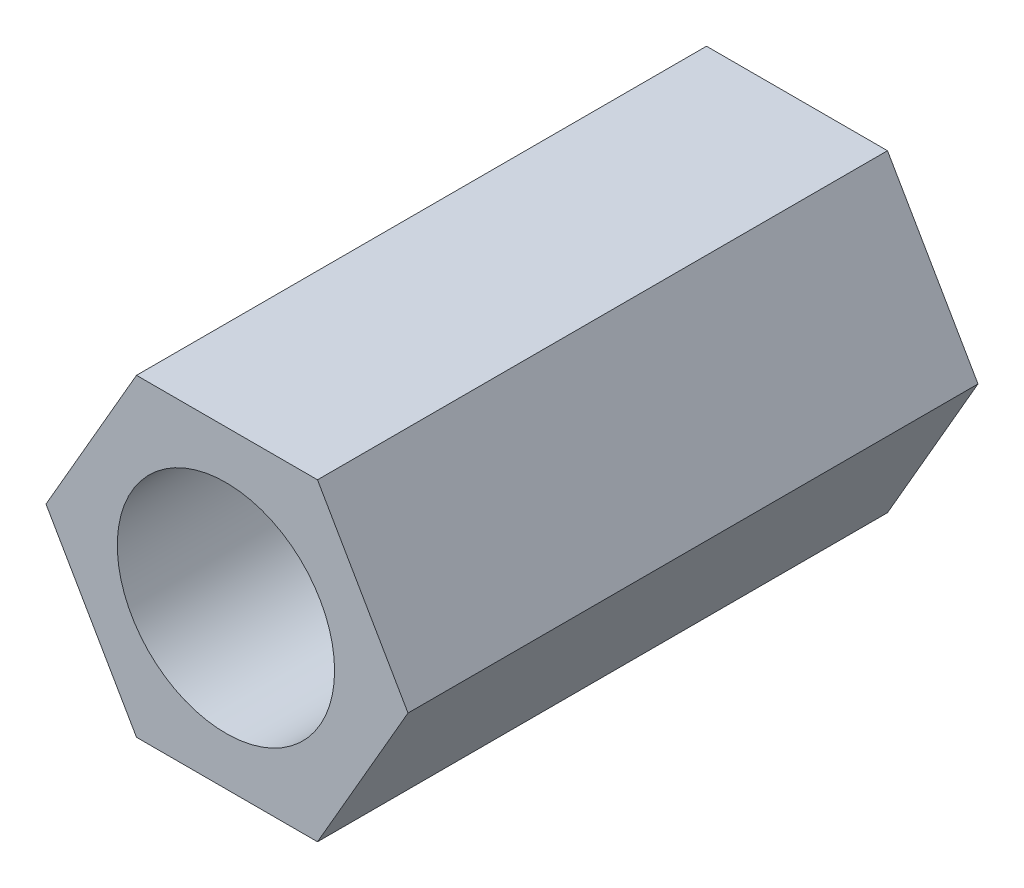
SolidWorks part; units mm, degrees
material "7075-T6 (SN)"
ref_plane "Front Plane" through (0, 0, 0) normal (0, 0, 1) x (1, 0, 0)
ref_plane "Top Plane" through (0, 0, 0) normal (0, 1, 0) x (1, 0, 0)
ref_plane "Right Plane" through (0, 0, 0) normal (1, 0, 0) x (0, 0, -1)
ref_plane "Plane1" through (0, 0, 40) normal (0, 0, 1) x (1, 0, 0)
sketch "Sketch1" plane through (0, 0, 40) normal (0, 0, 1) x (1, 0, 0)
  line L0 (-12.7017, 0) -> (-6.3509, -11)
  line L1 (-6.3509, -11) -> (6.3509, -11)
  line L2 (6.3509, -11) -> (12.7017, 0)
  line L3 (12.7017, 0) -> (6.3509, 11)
  line L4 (6.3509, 11) -> (-6.3509, 11)
  line L5 (-6.3509, 11) -> (-12.7017, 0)
extrude "Boss-Extrude1" add sketch "Sketch1" against normal blind 40
sketch "Sketch4" plane through (0, 0, 0) normal (0, 1, 0) x (1, 0, 0)
  line L0 (-0.0748, 0) -> (-0.0748, -40)
  line L1 (-0.0748, -40) -> (7.55, -40)
  line L2 (7.55, -40) -> (7.55, -25.17)
  line L3 (7.55, -25.17) -> (5, -25.17)
  line L4 (5, -25.17) -> (5, -21.69)
  line L5 (-0.0748, -0.3175) -> (-0.0748, -40) construction
  line L6 (5.9156, 0) -> (-0.0748, 0)
  arc A0 (5, -21.69) -> (3.855, -19.882) centre (3, -21.69) ccw
  arc A1 (3.855, -19.882) -> (2.3143, -15.8729) centre (5.1845, -17.0705) cw
  arc A2 (2.3143, -15.8729) -> (5.9156, 0) centre (-41.5228, 2.418) ccw
revolve "Cut-Revolve1" cut sketch "Sketch4" angle 360 about L5
